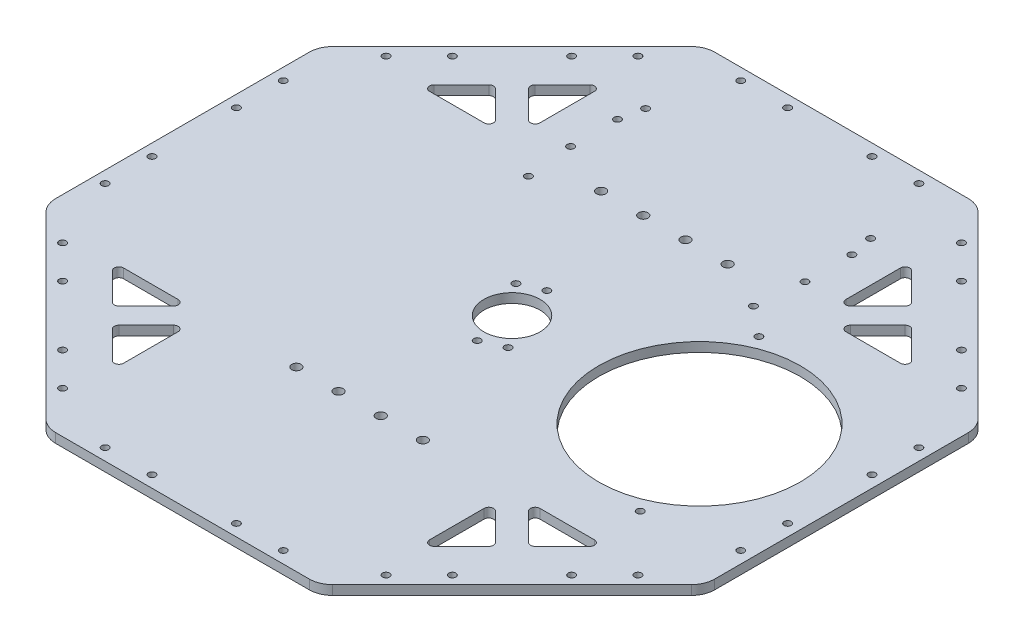
SolidWorks part; units mm, degrees
ref_plane "前视基准面" through (0, 0, 0) normal (0, 0, 1) x (1, 0, 0)
ref_plane "上视基准面" through (0, 0, 0) normal (0, 1, 0) x (1, 0, 0)
ref_plane "右视基准面" through (0, 0, 0) normal (1, 0, 0) x (0, 0, -1)
other "Configuration Table"
sketch "草图1" plane through (0, 0, 0) normal (0, 1, 0) x (1, 0, 0)
  line L0 (-138.5819, 0) -> (138.5819, 0) construction
  line L1 (0, 138.5819) -> (0, -138.5819) construction
  line L2 (-57.4025, 138.5819) -> (57.4025, 138.5819) construction
  line L3 (57.4025, 138.5819) -> (138.5819, 57.4025) construction
  line L4 (138.5819, 57.4025) -> (138.5819, -57.4025) construction
  line L5 (138.5819, -57.4025) -> (57.4025, -138.5819) construction
  line L6 (-57.4025, -138.5819) -> (57.4025, -138.5819) construction
  line L7 (-57.4025, -138.5819) -> (-138.5819, -57.4025) construction
  line L8 (-138.5819, -57.4025) -> (-138.5819, 57.4025) construction
  line L9 (-138.5819, 57.4025) -> (-57.4025, 138.5819) construction
  line L10 (0, 0) -> (-6.4, 14.6642) construction
  line L11 (-10.9815, 12.6647) -> (-6.4, 14.6642) construction
  line L12 (0, 0) -> (67.2, 29.3285) construction
  line L13 (-140.5819, 58.2309) -> (-58.2309, 140.5819)
  line L14 (-58.2309, 140.5819) -> (58.2309, 140.5819)
  line L15 (58.2309, 140.5819) -> (140.5819, 58.2309)
  line L16 (140.5819, 58.2309) -> (140.5819, -58.2309)
  line L17 (140.5819, -58.2309) -> (58.2309, -140.5819)
  line L18 (-58.2309, -140.5819) -> (58.2309, -140.5819)
  line L19 (-58.2309, -140.5819) -> (-140.5819, -58.2309)
  line L20 (-140.5819, -58.2309) -> (-140.5819, 58.2309)
  circle A0 centre (0, 0) radius 12
  circle A1 centre (-10.9815, 12.6647) radius 1.5
  circle A7 centre (80, 0) radius 32 construction
  circle A8 centre (-1.8185, 16.6638) radius 1.5
  circle A9 centre (1.8185, -16.6638) radius 1.5
  circle A10 centre (10.9815, -12.6647) radius 1.5
  point P3 (0, 0)
  point P6 (0, 0)
  point P9 (0, 138.5819)
  point P17 (0, -138.5819)
  dimension "D2" = 24
  dimension "D4" = 3
  dimension "D7" = 64
  dimension "D1" = 300
  dimension "D3" = 4.9988
  dimension "D5" = 16
  dimension "D6" = 80
  dimension "D8" = 2
extrude "凸台-拉伸1" add sketch "草图1" along normal blind 4
sketch "草图2" plane through (0, 4, 0) normal (0, 1, 0) x (1, 0, 0)
  line L0 (0, 0) -> (80, 0) construction
  line L2 (67.2, 29.3285) -> (0, 0) construction
  line L4 (99.6, -44.9092) -> (60.4, 44.9092) construction
  circle A0 centre (80, 0) radius 49 construction
  circle A3 centre (60.4, 44.9092) radius 1.5
  circle A5 centre (99.6, -44.9092) radius 1.5
  circle A6 centre (80, 0) radius 43
  circle A7 centre (80, 0) radius 32 construction
  dimension "D1" = 98
  dimension "D3" = 3
  dimension "D5" = 86
  dimension "D2" = 64
  dimension "D4" = 80
extrude "切除-拉伸1" cut sketch "草图2" against normal blind 10
sketch "草图3" plane through (0, 4, 0) normal (0, 1, 0) x (1, 0, 0)
  line L0 (-38, 135.5819) -> (-18, 135.5819) construction
  line L1 (0, 0) -> (37, 0) construction
  line L3 (-13, 138.5819) -> (-53, 138.5819) construction
  line L4 (-53, 138.5819) -> (-53, 132.5819) construction
  line L5 (-53, 132.5819) -> (-13, 132.5819) construction
  line L6 (-13, 132.5819) -> (-13, 138.5819) construction
  line L7 (0, 0) -> (0, 140.5819) construction
  line L8 (13, 132.5819) -> (13, 138.5819) construction
  line L9 (53, 132.5819) -> (13, 132.5819) construction
  line L10 (53, 138.5819) -> (53, 132.5819) construction
  line L11 (13, 138.5819) -> (53, 138.5819) construction
  line L12 (38, 135.5819) -> (18, 135.5819) construction
  line L13 (-35, 65) -> (-9, 65) construction
  line L30 (58.2309, 140.5819) -> (-58.2309, 140.5819) construction
  circle A2 centre (-38, 135.5819) radius 1.5
  circle A3 centre (-18, 135.5819) radius 1.5
  circle A4 centre (18, 135.5819) radius 1.5
  circle A5 centre (38, 135.5819) radius 1.5
  circle A76 centre (69.0008, 122.741) radius 1.5
  circle A77 centre (83.143, 108.5988) radius 1.5
  circle A78 centre (108.5988, 83.143) radius 1.5
  circle A79 centre (122.741, 69.0008) radius 1.5
  circle A80 centre (135.5819, 38) radius 1.5
  circle A81 centre (135.5819, 18) radius 1.5
  circle A82 centre (135.5819, -18) radius 1.5
  circle A83 centre (135.5819, -38) radius 1.5
  circle A84 centre (122.741, -69.0008) radius 1.5
  circle A85 centre (108.5988, -83.143) radius 1.5
  circle A86 centre (83.143, -108.5988) radius 1.5
  circle A87 centre (69.0008, -122.741) radius 1.5
  circle A88 centre (38, -135.5819) radius 1.5
  circle A89 centre (18, -135.5819) radius 1.5
  circle A90 centre (-18, -135.5819) radius 1.5
  circle A91 centre (-38, -135.5819) radius 1.5
  circle A92 centre (-69.0008, -122.741) radius 1.5
  circle A93 centre (-83.143, -108.5988) radius 1.5
  circle A94 centre (-108.5988, -83.143) radius 1.5
  circle A95 centre (-122.741, -69.0008) radius 1.5
  circle A96 centre (-135.5819, -38) radius 1.5
  circle A97 centre (-135.5819, -18) radius 1.5
  circle A98 centre (-135.5819, 18) radius 1.5
  circle A99 centre (-135.5819, 38) radius 1.5
  circle A100 centre (-122.741, 69.0008) radius 1.5
  circle A101 centre (-108.5988, 83.143) radius 1.5
  circle A102 centre (-83.143, 108.5988) radius 1.5
  circle A103 centre (-69.0008, 122.741) radius 1.5
  circle A105 centre (-27, 65) radius 2
  circle A106 centre (-9, 65) radius 2
  circle A107 centre (9, 65) radius 2
  circle A108 centre (27, 65) radius 2
  circle A109 centre (27, -65) radius 2
  circle A110 centre (9, -65) radius 2
  circle A111 centre (-9, -65) radius 2
  circle A112 centre (-27, -65) radius 2
  circle A113 centre (80, 0) radius 43 construction
  point P80 (0, 0)
  dimension "D2" = 3
  dimension "D10" = 4
  dimension "D1" = 20
  dimension "D3" = 5
  dimension "D4" = 18
  dimension "D5" = 6
  dimension "D6" = 40
  dimension "D7" = 5
  dimension "D9" = 65
  dimension "D11" = 18
  dimension "D12" = 8
  dimension "D13" = 9
  dimension "D15" = 2
  dimension "D8" = 8
extrude "切除-拉伸2" cut sketch "草图3" against normal blind 10
fillet "圆角3" radius 10 8 edges at (-140.5819, 2, -58.2309) (-58.2309, 2, -140.5819) (58.2309, 2, -140.5819) (140.5819, 2, -58.2309) (140.5819, 2, 58.2309) (58.2309, 2, 140.5819) (-140.5819, 2, 58.2309) (-58.2309, 2, 140.5819)
sketch "草图4" plane through (0, 0, 0) normal (0, -1, 0) x (1, 0, 0)
  line L0 (0, 0) -> (0, -80) construction
  line L1 (-50, -75) -> (-50, -95) construction
  line L2 (-50, -75) -> (-50, -60) construction
  line L3 (-50, -95) -> (-50, -100) construction
  line L4 (50, -75) -> (50, -95) construction
  line L6 (-48, -55) -> (48, -55) construction
  line L7 (-48, -55) -> (-48, -105) construction
  line L8 (-48, -105) -> (48, -105) construction
  line L9 (48, -55) -> (48, -105) construction
  line L10 (-48, -55) -> (48, -105) construction
  line L11 (-48, -105) -> (48, -55) construction
  circle A0 centre (-50, -75) radius 1.5
  circle A1 centre (-50, -95) radius 1.5
  circle A2 centre (50, -95) radius 1.5
  circle A3 centre (50, -75) radius 1.5
  circle A4 centre (-48, -55) radius 1.5
  circle A5 centre (48, -55) radius 1.5
  circle A6 centre (-48, -105) radius 1.5
  circle A7 centre (48, -105) radius 1.5
  dimension "D4" = 3
  dimension "D10" = 3
  dimension "D1" = 80
  dimension "D2" = 40
  dimension "D3" = 20
  dimension "D5" = 15
  dimension "D6" = 5
  dimension "D7" = 100
  dimension "D8" = 96
  dimension "D9" = 50
extrude "切除-拉伸3" cut sketch "草图4" against normal blind 10
sketch "草图5" plane through (0, 0, 0) normal (0, -1, 0) x (1, 0, 0)
  line L0 (0, 0) -> (37, 0) construction
  line L1 (0, 0) -> (0, 140.5819) construction
  line L2 (-54.0888, 140.5819) -> (54.0888, 140.5819) construction
  line L8 (61.1599, 137.653) -> (137.653, 61.1599) construction
  line L12 (0, 0) -> (99.4064, 99.4064) construction
  line L20 (65.2643, -72.3354) -> (65.2643, -105.2643)
  line L21 (65.2643, -105.2643) -> (81.7288, -88.7998)
  line L22 (105.2643, -65.2643) -> (72.3354, -65.2643)
  line L23 (-72.3354, -65.2643) -> (-65.2643, -65.2643) construction
  line L24 (137.653, -61.1599) -> (61.1599, -137.653) construction
  line L25 (65.2643, -65.2643) -> (99.4064, -99.4064) construction
  line L35 (65.2643, -72.3354) -> (81.7288, -88.7998)
  line L36 (72.3354, -65.2643) -> (88.7998, -81.7288)
  line L37 (61.7288, -68.7998) -> (95.8709, -102.942) construction
  line L38 (68.7998, -61.7288) -> (102.942, -95.8709) construction
  line L39 (88.7998, -81.7288) -> (105.2643, -65.2643)
  line L40 (65.2643, -72.3354) -> (65.2643, -65.2643) construction
  line L41 (72.3354, -65.2643) -> (65.2643, -65.2643) construction
  line L42 (65.2643, 72.3354) -> (81.7288, 88.7998)
  line L43 (65.2643, 105.2643) -> (81.7288, 88.7998)
  line L44 (65.2643, 72.3354) -> (65.2643, 105.2643)
  line L45 (88.7998, 81.7288) -> (105.2643, 65.2643)
  line L46 (72.3354, 65.2643) -> (88.7998, 81.7288)
  line L47 (105.2643, 65.2643) -> (72.3354, 65.2643)
  line L48 (-65.2643, -72.3354) -> (-65.2643, -65.2643) construction
  line L49 (-65.2643, -65.2643) -> (-99.4064, -99.4064) construction
  line L50 (-105.2643, 65.2643) -> (-72.3354, 65.2643)
  line L51 (-72.3354, 65.2643) -> (-88.7998, 81.7288)
  line L52 (-88.7998, 81.7288) -> (-105.2643, 65.2643)
  line L53 (-65.2643, 72.3354) -> (-65.2643, 105.2643)
  line L54 (-65.2643, 105.2643) -> (-81.7288, 88.7998)
  line L55 (-65.2643, 72.3354) -> (-81.7288, 88.7998)
  line L56 (-88.7998, -81.7288) -> (-105.2643, -65.2643)
  line L57 (-72.3354, -65.2643) -> (-88.7998, -81.7288)
  line L58 (-65.2643, -72.3354) -> (-81.7288, -88.7998)
  line L59 (-105.2643, -65.2643) -> (-72.3354, -65.2643)
  line L60 (-65.2643, -105.2643) -> (-81.7288, -88.7998)
  line L61 (-65.2643, -72.3354) -> (-65.2643, -105.2643)
  circle A0 centre (80, 0) radius 43 construction
  dimension "D1" = 40
  dimension "D2" = 20
  dimension "D3" = 5
  dimension "D4" = 5
extrude "切除-拉伸4" cut sketch "草图5" against normal blind 10
fillet "圆角4" radius 2 24 edges at (65.2643, 2, -72.3354) (81.7288, 2, -88.7998) (65.2643, 2, -105.2643) (-72.3354, 2, 65.2643) (-105.2643, 2, 65.2643) (-88.7998, 2, 81.7288) (-81.7288, 2, -88.7998) (-65.2643, 2, -72.3354) (-65.2643, 2, -105.2643) (-65.2643, 2, 105.2643) (-65.2643, 2, 72.3354) (-81.7288, 2, 88.7998) (72.3354, 2, -65.2643) (105.2643, 2, -65.2643) (88.7998, 2, -81.7288) (81.7288, 2, 88.7998) (65.2643, 2, 72.3354) (65.2643, 2, 105.2643) (105.2643, 2, 65.2643) (72.3354, 2, 65.2643) (88.7998, 2, 81.7288) (-88.7998, 2, -81.7288) (-72.3354, 2, -65.2643) (-105.2643, 2, -65.2643)
